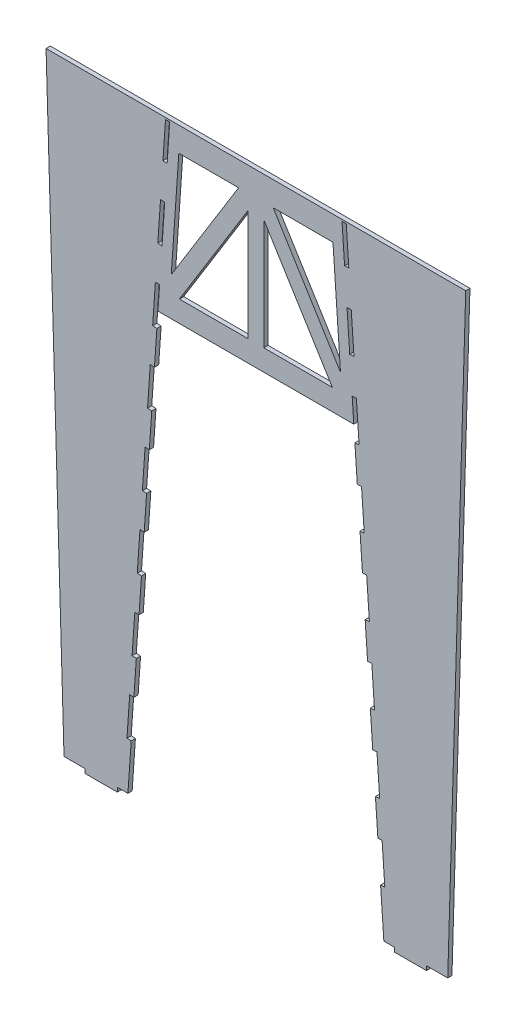
SolidWorks part; units mm, degrees
material "A-Glass Fiber"
ref_plane "Front Plane" through (0, 0, 0) normal (0, 0, 1) x (1, 0, 0)
ref_plane "Top Plane" through (0, 0, 0) normal (0, 1, 0) x (1, 0, 0)
ref_plane "Right Plane" through (0, 0, 0) normal (1, 0, 0) x (0, 0, -1)
sketch "Sketch1" plane through (0, 0, 0) normal (0, 0, 1) x (1, 0, 0)
  line L0 (-288.2759, 0) -> (288.2759, 0) construction
  line L1 (-215.8925, 1465.1633) -> (215.8925, 1465.1633)
  line L2 (0, 0) -> (0, 1733.4513) construction
  line L3 (19.05, 1104.9) -> (205.6376, 1104.9)
  line L4 (202.8026, 1145.716) -> (41.4459, 1406.7433)
  line L5 (205.6376, 1104.9) -> (19.05, 1406.7433) construction
  line L6 (205.6376, 1104.9) -> (184.6725, 1406.7433)
  line L7 (183.2417, 1104.9) -> (15.2162, 1376.7154)
  line L8 (19.05, 1406.7433) -> (19.05, 1104.9)
  line L9 (184.6725, 1406.7433) -> (19.05, 1406.7433)
  line L10 (306.6278, 17.4764) -> (234.6272, 1054.1)
  line L12 (459.7218, 17.4764) -> (502.7833, 1465.1633)
  line L13 (459.7218, 7.3164) -> (520.3601, 2060.228) construction
  line L15 (266.6925, 1465.1633) -> (368.5375, 1465.1633)
  line L16 (-237.2124, 1016.8799) -> (-230.6925, 1110.7494) construction
  line L18 (237.2124, 1016.8799) -> (230.6925, 1110.7494) construction
  line L19 (-408.9218, 7.3164) -> (-332.1008, 7.3164)
  line L20 (-502.7833, 1465.1633) -> (-215.8925, 1465.1633)
  line L22 (408.9218, 7.3164) -> (332.7218, 7.3164)
  line L24 (-408.9218, 17.4764) -> (-408.9218, 7.3164) construction
  line L30 (-408.9218, 17.4764) -> (-408.9218, 7.3164)
  line L31 (502.7833, 1465.1633) -> (368.5375, 1465.1633)
  line L32 (-332.1008, 17.4764) -> (-332.1008, 7.3164) construction
  line L33 (-332.1008, 17.4764) -> (-332.1008, 7.3164)
  line L34 (408.9218, 17.4764) -> (408.9218, 7.3164) construction
  line L35 (408.9218, 17.4764) -> (408.9218, 7.3164)
  line L40 (332.7218, 17.4764) -> (332.7218, 7.3164) construction
  line L43 (332.7218, 17.4764) -> (332.7218, 7.3164)
  line L44 (459.7218, 17.4764) -> (408.9218, 17.4764) construction
  line L45 (459.7218, 17.4764) -> (408.9218, 17.4764)
  line L49 (-408.9218, 17.4764) -> (-459.7218, 17.4764)
  line L52 (-332.1008, 17.4764) -> (-306.6278, 17.4764)
  line L53 (332.7218, 17.4764) -> (306.6278, 17.4764)
  line L55 (-459.7218, 17.4764) -> (-502.7833, 1465.1633)
  line L56 (-459.7218, 7.3164) -> (-520.3601, 2060.228) construction
  line L81 (215.8925, 1465.1633) -> (266.6925, 1465.1633)
  line L90 (234.6272, 1054.1) -> (-234.6272, 1054.1)
  line L100 (-234.6272, 1054.1) -> (-306.6278, 17.4764)
  line L124 (-184.6725, 1406.7433) -> (-19.05, 1406.7433)
  line L125 (-19.05, 1406.7433) -> (-19.05, 1104.9)
  line L126 (-183.2417, 1104.9) -> (-15.2162, 1376.7154)
  line L127 (-205.6376, 1104.9) -> (-19.05, 1406.7433) construction
  line L128 (-202.8026, 1145.716) -> (-41.4459, 1406.7433)
  line L129 (-205.6376, 1104.9) -> (-184.6725, 1406.7433)
  line L130 (-19.05, 1104.9) -> (-205.6376, 1104.9)
  point P0 (0, 0)
  point P3 (0, 0)
  point P106 (0, 0)
  point P118 (0, 1054.1)
  dimension "D6" = 25.4
  dimension "D7" = 50.8
  dimension "D8" = 58.42
  dimension "D9" = 19.05
  dimension "D19" = 288.2759
  dimension "D22" = 19.05
  dimension "D23" = 19.05
  dimension "D24" = 1054.1
  dimension "D49" = 50.8
extrude "Boss-Extrude1" add sketch "Sketch1" along normal blind 10.16
fillet "Fillet1" [suppressed] radius 19.05
sketch "Sketch2" plane through (0, 0, 0) normal (0, 0, 1) x (1, 0, 0)
  line L18 (-222.6942, 1372.2749) -> (-212.5765, 1371.5721) construction
  line L56 (-216.5353, 1460.9479) -> (-222.6942, 1372.2749) construction
  line L57 (-212.5765, 1371.5721) -> (-206.3688, 1460.9479) construction
  line L58 (-206.3688, 1460.9479) -> (-216.5353, 1460.9479) construction
  line L59 (-222.6942, 1372.2749) -> (-212.5765, 1371.5721)
  line L61 (-216.5353, 1460.9479) -> (-222.6942, 1372.2749)
  line L63 (-212.5765, 1371.5721) -> (-206.3688, 1460.9479)
  line L176 (-206.3688, 1460.9479) -> (-216.5353, 1460.9479)
  line L181 (-224.8945, 1194.226) -> (-235.0121, 1194.9287) construction
  line L194 (-224.8945, 1194.226) -> (-218.3727, 1288.1221) construction
  line L199 (-218.3727, 1288.1221) -> (-228.4904, 1288.8248) construction
  line L208 (-228.4904, 1288.8248) -> (-235.0121, 1194.9287) construction
  line L213 (-224.8945, 1194.226) -> (-235.0121, 1194.9287)
  line L330 (-224.8945, 1194.226) -> (-218.3727, 1288.1221)
  line L331 (-218.3727, 1288.1221) -> (-228.4904, 1288.8248)
  line L332 (-228.4904, 1288.8248) -> (-235.0121, 1194.9287)
  line L333 (224.8945, 1194.226) -> (235.0121, 1194.9287) construction
  line L334 (235.0121, 1194.9287) -> (228.4904, 1288.8248) construction
  line L335 (218.3727, 1288.1221) -> (224.8945, 1194.226) construction
  line L336 (228.4904, 1288.8248) -> (218.3727, 1288.1221) construction
  line L337 (212.5765, 1371.5721) -> (222.6942, 1372.2749) construction
  line L338 (206.3688, 1460.9479) -> (212.5765, 1371.5721) construction
  line L339 (216.5353, 1460.9479) -> (206.3688, 1460.9479) construction
  line L340 (222.6942, 1372.2749) -> (216.5353, 1460.9479) construction
  line L341 (224.8945, 1194.226) -> (235.0121, 1194.9287)
  line L342 (235.0121, 1194.9287) -> (228.4904, 1288.8248)
  line L343 (218.3727, 1288.1221) -> (224.8945, 1194.226)
  line L344 (228.4904, 1288.8248) -> (218.3727, 1288.1221)
  line L345 (212.5765, 1371.5721) -> (222.6942, 1372.2749)
  line L346 (206.3688, 1460.9479) -> (212.5765, 1371.5721)
  line L347 (216.5353, 1460.9479) -> (206.3688, 1460.9479)
  line L348 (222.6942, 1372.2749) -> (216.5353, 1460.9479)
  line L349 (-240.8102, 1111.4521) -> (-247.33, 1017.5826) construction
  line L350 (-247.33, 1017.5826) -> (-237.2124, 1016.8799) construction
  line L351 (-230.6925, 1110.7494) -> (-240.8102, 1111.4521) construction
  line L353 (-240.8102, 1111.4521) -> (-247.33, 1017.5826)
  line L354 (-247.33, 1017.5826) -> (-237.2124, 1016.8799)
  line L355 (-230.6925, 1110.7494) -> (-240.8102, 1111.4521)
  line L357 (237.2124, 1016.8799) -> (247.33, 1017.5826) construction
  line L358 (247.33, 1017.5826) -> (240.8102, 1111.4521) construction
  line L360 (240.8102, 1111.4521) -> (230.6925, 1110.7494) construction
  line L361 (237.2124, 1016.8799) -> (247.33, 1017.5826)
  line L362 (247.33, 1017.5826) -> (240.8102, 1111.4521)
  line L364 (240.8102, 1111.4521) -> (230.6925, 1110.7494)
  line L365 (-306.6278, 17.4764) -> (-234.6272, 1054.1)
  line L366 (-234.6272, 1054.1) -> (234.6272, 1054.1)
  line L367 (234.6272, 1054.1) -> (306.6278, 17.4764)
  line L372 (408.9218, 17.4764) -> (459.7218, 17.4764)
  line L373 (459.7218, 17.4764) -> (502.7833, 1465.1633)
  line L374 (502.7833, 1465.1633) -> (-502.7833, 1465.1633)
  line L375 (-502.7833, 1465.1633) -> (-459.7218, 17.4764)
  line L376 (-459.7218, 17.4764) -> (-408.9218, 17.4764)
  line L377 (-408.9218, 17.4764) -> (-408.9218, 7.3164)
  line L378 (-408.9218, 7.3164) -> (-332.1008, 7.3164)
  line L379 (-332.1008, 7.3164) -> (-332.1008, 17.4764)
  line L380 (-332.1008, 17.4764) -> (-306.6278, 17.4764)
  line L381 (-298.8019, 130.1492) -> (-292.2913, 223.886)
  line L405 (-243.0122, 933.3767) -> (-253.1299, 934.0795) construction
  line L406 (-253.1299, 934.0795) -> (-259.648, 840.2365) construction
  line L407 (-249.5303, 839.5337) -> (-259.648, 840.2365) construction
  line L408 (-243.0122, 933.3767) -> (-253.1299, 934.0795)
  line L417 (-253.1299, 934.0795) -> (-259.648, 840.2365)
  line L418 (-249.5303, 839.5337) -> (-259.648, 840.2365)
  line L419 (243.0122, 933.3767) -> (253.1299, 934.0795) construction
  line L420 (253.1299, 934.0795) -> (259.648, 840.2365) construction
  line L421 (249.5303, 839.5337) -> (259.648, 840.2365) construction
  line L422 (243.0122, 933.3767) -> (253.1299, 934.0795)
  line L423 (253.1299, 934.0795) -> (259.648, 840.2365)
  line L424 (249.5303, 839.5337) -> (259.648, 840.2365)
  line L425 (-267.6517, 578.6314) -> (-277.7694, 579.3341) construction
  line L426 (-255.332, 756.0041) -> (-265.4497, 756.7068) construction
  line L427 (-265.4497, 756.7068) -> (-271.9659, 662.8903) construction
  line L428 (-261.8482, 662.1876) -> (-271.9659, 662.8903) construction
  line L429 (-277.7694, 579.3341) -> (-284.2838, 485.5442) construction
  line L430 (-274.1661, 484.8415) -> (-284.2838, 485.5442) construction
  line L431 (-274.1661, 484.8415) -> (-284.2838, 485.5442)
  line L432 (-277.7694, 579.3341) -> (-284.2838, 485.5442)
  line L433 (-267.6517, 578.6314) -> (-277.7694, 579.3341)
  line L434 (-261.8482, 662.1876) -> (-271.9659, 662.8903)
  line L435 (-265.4497, 756.7068) -> (-271.9659, 662.8903)
  line L436 (-255.332, 756.0041) -> (-265.4497, 756.7068)
  line L437 (261.8482, 662.1876) -> (271.9659, 662.8903) construction
  line L438 (255.332, 756.0041) -> (265.4497, 756.7068) construction
  line L439 (265.4497, 756.7068) -> (271.9659, 662.8903) construction
  line L440 (261.8482, 662.1876) -> (271.9659, 662.8903)
  line L449 (255.332, 756.0041) -> (265.4497, 756.7068)
  line L450 (265.4497, 756.7068) -> (271.9659, 662.8903)
  line L451 (274.1661, 484.8415) -> (284.2838, 485.5442) construction
  line L452 (277.7694, 579.3341) -> (284.2838, 485.5442) construction
  line L453 (267.6517, 578.6314) -> (277.7694, 579.3341) construction
  line L454 (274.1661, 484.8415) -> (284.2838, 485.5442)
  line L455 (277.7694, 579.3341) -> (284.2838, 485.5442)
  line L456 (267.6517, 578.6314) -> (277.7694, 579.3341)
  line L457 (-298.8019, 130.1492) -> (-308.9196, 130.8519) construction
  line L458 (-302.4089, 224.5888) -> (-308.9196, 130.8519) construction
  line L459 (-292.2913, 223.886) -> (-302.4089, 224.5888) construction
  line L460 (-286.484, 307.4953) -> (-296.6017, 308.1981) construction
  line L461 (-290.0892, 401.9615) -> (-296.6017, 308.1981) construction
  line L462 (-279.9715, 401.2587) -> (-290.0892, 401.9615) construction
  line L463 (-298.8019, 130.1492) -> (-308.9196, 130.8519)
  line L464 (-302.4089, 224.5888) -> (-308.9196, 130.8519)
  line L465 (-292.2913, 223.886) -> (-302.4089, 224.5888)
  line L466 (-286.484, 307.4953) -> (-296.6017, 308.1981)
  line L467 (-290.0892, 401.9615) -> (-296.6017, 308.1981)
  line L468 (-279.9715, 401.2587) -> (-290.0892, 401.9615)
  line L469 (286.484, 307.4953) -> (296.6017, 308.1981) construction
  line L470 (279.9715, 401.2587) -> (290.0892, 401.9615) construction
  line L471 (290.0892, 401.9615) -> (296.6017, 308.1981) construction
  line L472 (286.484, 307.4953) -> (296.6017, 308.1981)
  line L473 (279.9715, 401.2587) -> (290.0892, 401.9615)
  line L474 (290.0892, 401.9615) -> (296.6017, 308.1981)
  line L475 (298.8019, 130.1492) -> (308.9196, 130.8519) construction
  line L476 (302.4089, 224.5888) -> (308.9196, 130.8519) construction
  line L477 (292.2913, 223.886) -> (302.4089, 224.5888) construction
  line L478 (298.8019, 130.1492) -> (308.9196, 130.8519)
  line L479 (302.4089, 224.5888) -> (308.9196, 130.8519)
  line L480 (292.2913, 223.886) -> (302.4089, 224.5888)
  line L481 (-230.6925, 1110.7494) -> (-237.2124, 1016.8799)
  line L482 (243.0122, 933.3767) -> (249.5303, 839.5337)
  line L483 (255.332, 756.0041) -> (261.8482, 662.1876)
  line L484 (-249.5303, 839.5337) -> (-243.0122, 933.3767)
  line L485 (-261.8482, 662.1876) -> (-255.332, 756.0041)
  line L486 (267.6517, 578.6314) -> (274.1661, 484.8415)
  line L487 (-286.484, 307.4953) -> (-279.9715, 401.2587)
  line L488 (-274.1661, 484.8415) -> (-267.6517, 578.6314)
  line L489 (279.9715, 401.2587) -> (286.484, 307.4953)
  line L490 (292.2913, 223.886) -> (298.8019, 130.1492)
  line L492 (230.6925, 1110.7494) -> (237.2124, 1016.8799)
  line L499 (306.6278, 17.4764) -> (332.7218, 17.4764)
  line L500 (332.7218, 17.4764) -> (332.7218, 7.3164)
  line L501 (332.7218, 7.3164) -> (408.9218, 7.3164)
  line L502 (408.9218, 7.3164) -> (408.9218, 17.4764)
  dimension "D1" = 0
extrude "Cut-Extrude5" cut sketch "Sketch2" along normal blind 12.7
